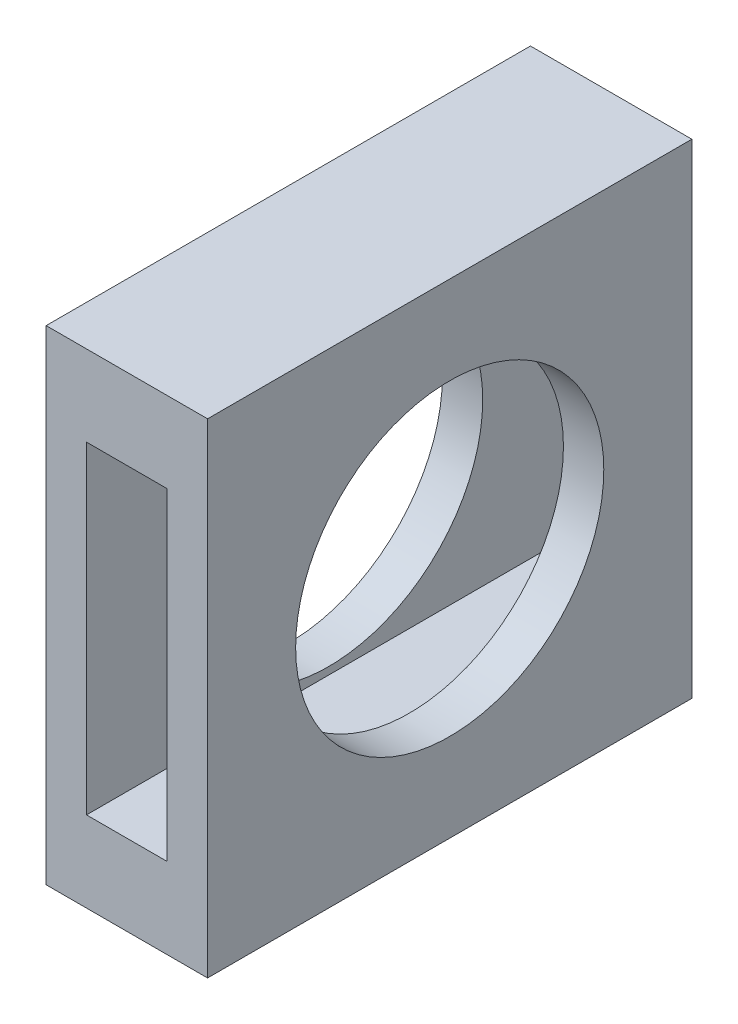
SolidWorks part; units mm, degrees
material "Delrin 2700 NC010，低粘度乙缩醛共聚物 (SS)"
ref_plane "前视基准面" through (0, 0, 0) normal (0, 0, 1) x (1, 0, 0)
ref_plane "上视基准面" through (0, 0, 0) normal (0, 1, 0) x (1, 0, 0)
ref_plane "右视基准面" through (0, 0, 0) normal (1, 0, 0) x (0, 0, -1)
sketch "草图1" plane through (0, 0, 0) normal (0, 0, 1) x (1, 0, 0)
  line L1 (-2.5, -10) -> (2.5, -10)
  line L2 (-2.5, -10) -> (-2.5, 10)
  line L3 (-2.5, 10) -> (2.5, 10)
  line L4 (2.5, -10) -> (2.5, 10)
  line L5 (-2.5, -10) -> (2.5, 10) construction
  line L6 (-2.5, 10) -> (2.5, -10) construction
  line L7 (-5, -15) -> (5, -15)
  line L8 (-5, -15) -> (-5, 15)
  line L9 (-5, 15) -> (5, 15)
  line L10 (5, -15) -> (5, 15)
  line L11 (-5, -15) -> (5, 15) construction
  line L12 (-5, 15) -> (5, -15) construction
  point P0 (0, 0)
  point P6 (0, 0)
  dimension "D1" = 5
  dimension "D2" = 10
  dimension "D3" = 20
  dimension "D4" = 30
extrude "凸台-拉伸1" add sketch "草图1" along normal mid plane 30
sketch "草图2" plane through (5, 0, 0) normal (1, 0, 0) x (0, 0, -1)
  circle A0 centre (0, 0) radius 9.5444
extrude "切除-拉伸1" cut sketch "草图2" against normal blind 30
